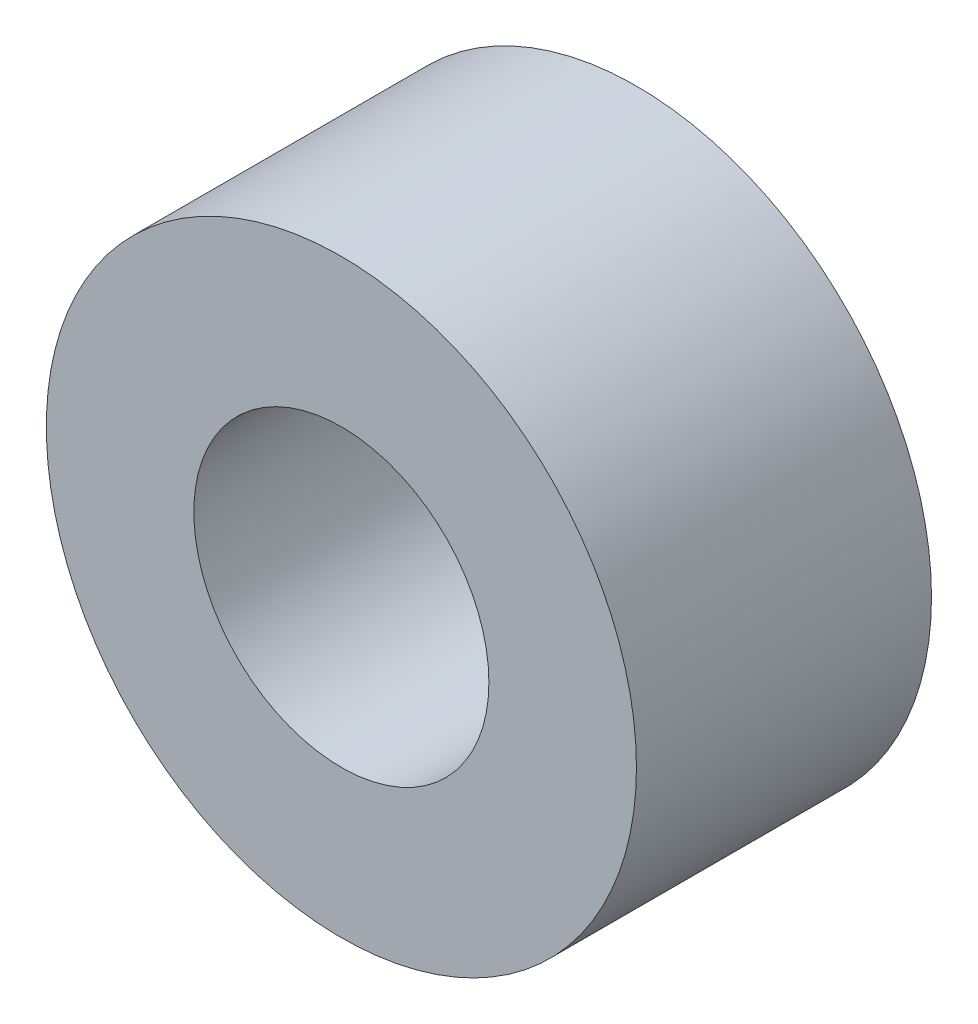
SolidWorks part; units mm, degrees
ref_plane "Front Plane" through (0, 0, 0) normal (0, 0, 1) x (1, 0, 0)
ref_plane "Top Plane" through (0, 0, 0) normal (0, 1, 0) x (1, 0, 0)
ref_plane "Right Plane" through (0, 0, 0) normal (1, 0, 0) x (0, 0, -1)
sketch "Sketch2" plane through (0, 0, 0) normal (0, 0, 1) x (1, 0, 0)
  circle A0 centre (0, 0) radius 3.175
  circle A1 centre (0, 0) radius 1.5875
  dimension "D1" = 6.35
  dimension "D2" = 3.175
extrude "Boss-Extrude1" add sketch "Sketch2" along normal blind 3.175
